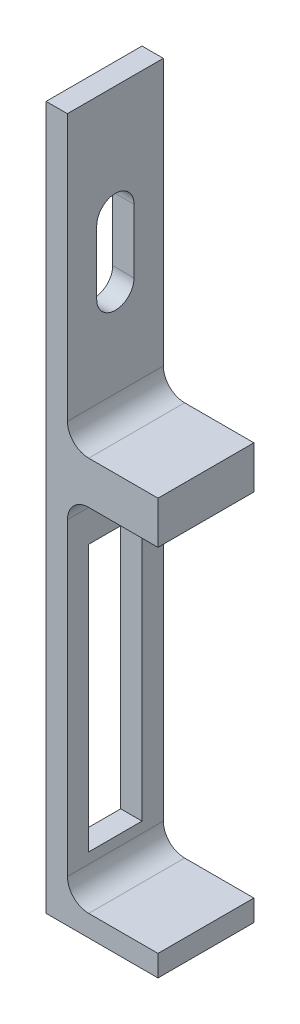
SolidWorks part; units mm, degrees
material "ПВХ Жесткий"
ref_plane "Спереди" through (0, 0, 0) normal (0, 0, 1) x (1, 0, 0)
ref_plane "Сверху" through (0, 0, 0) normal (0, 1, 0) x (1, 0, 0)
ref_plane "Справа" through (0, 0, 0) normal (1, 0, 0) x (0, 0, -1)
sketch "Эскиз1" plane through (0, 0, 0) normal (0, 0, 1) x (1, 0, 0)
  line L0 (0, 0) -> (10.5, 0)
  line L1 (10.5, 0) -> (10.5, 2)
  line L2 (10.5, 2) -> (2, 2)
  line L3 (2, 2) -> (2, 66)
  line L4 (2, 66) -> (0, 66)
  line L5 (0, 66) -> (0, 0)
  dimension "D1" = 2
  dimension "D2" = 66
  dimension "D3" = 10.5
extrude "Бобышка-Вытянуть1" add sketch "Эскиз1" along normal blind 9
sketch "Эскиз2" plane through (2, 0, 0) normal (1, 0, 0) x (0, 0, -1)
  line L0 (-4.5, 66) -> (-4.5, 2) construction
  line L1 (-9, 66) -> (0, 66) construction
  line L2 (-9, 2) -> (0, 2) construction
ref_plane "Плоскость1" through (0, 0, 4.5) normal (0, 0, 1) x (0, -1, 0)
sketch "Эскиз3" plane through (0, 0, 0) normal (-1, 0, 0) x (0, 0, 1)
  line L0 (9, 66) -> (0, 66) construction
  line L1 (4.5, 66) -> (4.5, 2) construction
  line L2 (4.5, 66) -> (4.5, 2) construction
  circle A1 centre (4.5, 52.52) radius 1.75
  dimension "D1" = 13.48
  dimension "D2" = 3.5
sketch "Эскиз4" plane through (0, 0, 0) normal (-1, 0, 0) x (0, 0, 1)
  line L0 (4.5, 55.52) -> (4.5, 49.52) construction
  line L1 (6.25, 55.52) -> (6.25, 49.52)
  line L2 (2.75, 55.52) -> (2.75, 49.52)
  line L3 (4.5, 66) -> (4.5, 43.3234) construction
  line L4 (9, 66) -> (0, 66) construction
  circle A0 centre (4.5, 52.52) radius 1.75 construction
  circle A1 centre (4.5, 52.52) radius 1.75 construction
  arc A2 (6.25, 55.52) -> (2.75, 55.52) centre (4.5, 55.52) ccw
  arc A3 (2.75, 49.52) -> (6.25, 49.52) centre (4.5, 49.52) ccw
  point P5 (4.5, 52.52)
  dimension "D1" = 6
extrude "Вырез-Вытянуть2" cut sketch "Эскиз4" against normal through all
sketch "Эскиз5" plane through (0, 0, 9) normal (0, 0, 1) x (1, 0, 0)
  line L0 (2, 2) -> (2, 66) construction
  line L1 (10.5, 2) -> (2, 2) construction
  line L2 (2, 2) -> (2, 9)
  line L3 (10.5, 2) -> (2, 2)
  line L4 (10.5, 2) -> (2, 9)
  dimension "D1" = 7
sketch "Эскиз6" plane through (2, 0, 0) normal (1, 0, 0) x (0, 0, -1)
  line L0 (-7, 5) -> (-2, 5)
  line L1 (-7, 5) -> (-7, 30)
  line L2 (-2, 5) -> (-2, 30)
  line L3 (-7, 30) -> (-2, 30)
  line L4 (-4.5, 30) -> (-4.5, 5) construction
  line L5 (-4.5, 66) -> (-4.5, 2) construction
  line L6 (-9, 2) -> (-9, 66) construction
  line L7 (-9, 2) -> (0, 2) construction
  dimension "D1" = 2
  dimension "D2" = 3
  dimension "D3" = 25
extrude "Вырез-Вытянуть3" cut sketch "Эскиз6" against normal through all
fillet "Скругление1" radius 2 1 edges at (2, 2, 4.5)
sketch "Эскиз7" plane through (0, 0, 9) normal (0, 0, 1) x (1, 0, 0)
  line L0 (2, 39) -> (2, 35)
  line L1 (2, 39) -> (10.5, 39)
  line L2 (2, 35) -> (10.5, 35)
  line L3 (10.5, 39) -> (10.5, 35)
  line L4 (2, 4) -> (2, 66) construction
  line L5 (0, 0) -> (10.5, 0) construction
  line L6 (10.5, 0) -> (10.5, 2) construction
  dimension "D1" = 35
  dimension "D2" = 4
extrude "Бобышка-Вытянуть2" add sketch "Эскиз7" against normal up to surface (9 mm away) up to face at (4.0837, 19.9408, 0)
fillet "Скругление2" radius 2 2 edges at (2, 39, 4.5) (2, 35, 4.5)
